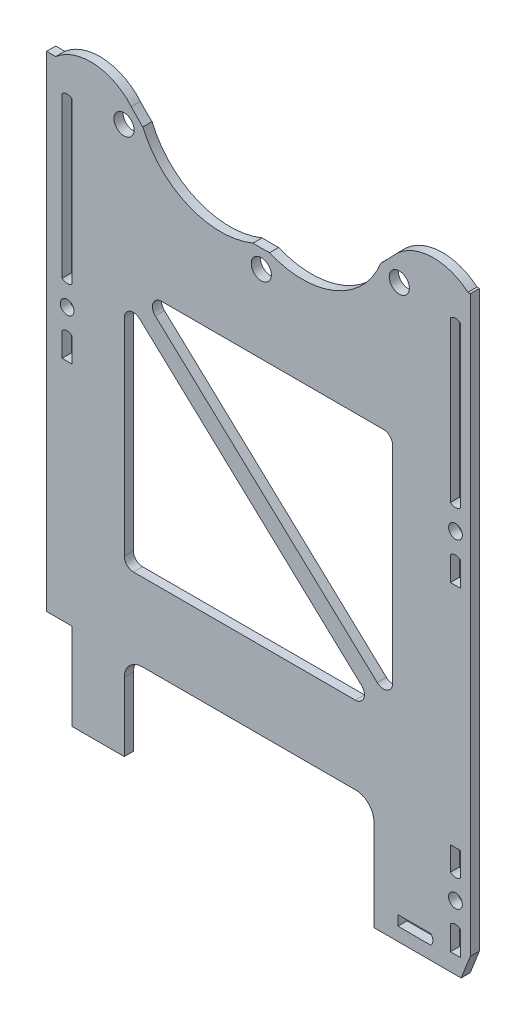
SolidWorks part; units mm, degrees
ref_plane "前视基准面" through (0, 0, 0) normal (0, 0, 1) x (1, 0, 0)
ref_plane "上视基准面" through (0, 0, 0) normal (0, 1, 0) x (1, 0, 0)
ref_plane "右视基准面" through (0, 0, 0) normal (1, 0, 0) x (0, 0, -1)
sketch "草图3" plane through (0, 0, 0) normal (0, 0, 1) x (1, 0, 0)
  line L8 (-41.4, -74.8902) -> (-41.4, -93.8902)
  line L12 (-42.5, -14.9402) -> (-41.8015, -14.9402) construction
  line L111 (-43.6, -9.9902) -> (-43.6, 25.0098)
  line L119 (-41.4, -19.8902) -> (-41.4, -25.1902)
  line L120 (-41.4, -25.1902) -> (-43.6, -25.1902)
  line L121 (-43.6, -25.1902) -> (-43.6, -19.8902)
  line L124 (37.1, -93.8902) -> (29.9, -93.8902)
  line L136 (37.1, -96.0902) -> (29.9, -96.0902)
  line L147 (30, -93.9902) -> (30, -95.9902) construction
  line L148 (29.9, -96.0902) -> (29.9, -93.8902)
  line L152 (-41.4, 25.0098) -> (-41.4, -9.9902)
  line L153 (37, -96.0902) -> (37.1, -96.0902) construction
  line L154 (37, -93.9902) -> (37, -95.9902) construction
  line L155 (37, -95.9902) -> (37, -96.0902) construction
  line L157 (43.6, -25.1902) -> (43.6, -19.8902)
  line L158 (41.4, -25.1902) -> (43.6, -25.1902)
  line L159 (41.4, -19.8902) -> (41.4, -25.1902)
  line L180 (0, 10.5098) -> (0, 13.5) construction
  line L187 (24.6413, -97.9902) -> (24.6413, -93.8902)
  line L198 (24.6413, -97.9902) -> (24.6413, -98.9902)
  line L199 (24.6413, -98.9902) -> (43.7413, -98.9902)
  line L209 (42.5, -9.9902) -> (42.5, -19.8902) construction
  line L212 (0, 56) -> (31.7001, 27.6918) construction
  line L213 (0, 56) -> (28.5728, 24.6019) construction
  line L218 (-45, 31.3171) -> (-47, 31.3171)
  line L221 (45.23, 31.7412) -> (45.7413, 31.7412)
  line L223 (45.7413, -93.8902) -> (43.7413, -98.9902)
  line L224 (45.7413, 31.7412) -> (45.7413, -93.8902)
  line L227 (43.6, -80.0902) -> (41.4, -74.8902) construction
  line L228 (43.6, -74.8902) -> (41.4, -80.0902) construction
  line L229 (42.5, -79.9902) -> (42.5, -74.9902) construction
  line L230 (43.6, -80.0902) -> (43.6, -89.8902) construction
  line L231 (43.6, -95.1902) -> (43.6, -89.8902)
  line L232 (41.4, -95.1902) -> (43.6, -95.1902)
  line L233 (41.4, -89.8902) -> (41.4, -95.1902)
  line L234 (41.4, -74.8902) -> (41.4, -80.0902)
  line L235 (43.6, -74.8902) -> (43.6, -80.0902)
  line L236 (43.6, -74.8902) -> (41.4, -74.8902)
  line L237 (42.5, -79.9902) -> (42.5, -89.8902) construction
  line L239 (-47, 31.3171) -> (-47, -74.8902)
  line L240 (-47, -74.8902) -> (-41.4, -74.8902)
  line L249 (-30, -93.8902) -> (-30, -78.8902)
  line L251 (41.4, 25.0098) -> (41.4, -9.9902)
  line L254 (43.6, -9.9902) -> (43.6, 25.0098)
  line L259 (-32, -1.5) -> (30.7413, -1.5) construction
  line L260 (-32, -1.5) -> (-32, -59.8902) construction
  line L261 (-32, -59.8902) -> (30.7413, -59.8902) construction
  line L262 (30.7413, -1.5) -> (30.7413, -59.8902) construction
  line L263 (24.6413, -78.8902) -> (24.6413, -93.8902)
  line L264 (-32, -1.5) -> (30.7413, -59.8902) construction
  line L265 (-21.8305, -3.5) -> (26.7413, -3.5)
  line L266 (28.7413, -5.5) -> (28.7413, -50.7034)
  line L267 (-23.1931, -6.9641) -> (25.3787, -52.1675)
  line L268 (-26.6375, -9.2228) -> (21.9343, -54.4261)
  line L269 (-28, -57.8902) -> (20.5718, -57.8902)
  line L270 (-30, -10.6868) -> (-30, -55.8902)
  line L271 (28.7413, -3.5) -> (28.7413, -55.2968) construction
  line L272 (-26.9153, -3.5) -> (28.7413, -3.5) construction
  line L273 (-26.9153, -3.5) -> (28.7413, -55.2968) construction
  line L274 (-30, -6.0934) -> (25.6565, -57.8902) construction
  line L275 (-30, -57.8902) -> (25.6565, -57.8902) construction
  line L276 (-30, -6.0934) -> (-30, -57.8902) construction
  line L277 (-41.4, -93.8902) -> (-30, -93.8902)
  line L278 (-26, -74.8902) -> (20.6413, -74.8902)
  arc A14 (-43.6, -19.8902) -> (-41.4, -19.8902) centre (-42.5, -20.9902) cw
  arc A15 (41.4, -19.8902) -> (43.6, -19.8902) centre (42.5, -20.9902) cw
  circle A17 centre (0, 13.5) radius 2.2
  circle A18 centre (-30.052, 25.948) radius 2.2
  circle A24 centre (30.2, 26.0826) radius 2.2
  arc A29 (37.1, -93.8902) -> (37.1, -96.0902) centre (36, -94.9902) cw
  circle A40 centre (42.5, -14.9402) radius 1.5
  circle A41 centre (-42.5, -14.9402) radius 1.5
  arc A43 (-25.9127, 27.5258) -> (-1.8098, 17.5426) centre (-8.8696, 34.5856) ccw
  arc A44 (1.8098, 17.5426) -> (26.1792, 27.7706) centre (9.013, 34.5255) ccw
  arc A46 (-25.9127, 27.5258) -> (-28.4742, 30.0873) centre (0, 56) cw
  arc A47 (-1.8098, 17.5426) -> (1.8098, 17.5426) centre (0, 56) ccw
  circle A52 centre (0, 56) radius 38.5 construction
  circle A53 centre (0, 56) radius 42.5 construction
  arc A54 (26.1792, 27.7706) -> (28.7166, 30.3561) centre (0, 56) ccw
  arc A55 (28.7166, 30.3561) -> (45.23, 31.7412) centre (37.6658, 22.7919) cw
  arc A56 (-28.4742, 30.0873) -> (-45, 31.3171) centre (-37.352, 22.4393) ccw
  arc A58 (41.4, -89.8902) -> (43.6, -89.8902) centre (42.5, -90.9902) cw
  arc A59 (41.4, -80.0902) -> (43.6, -80.0902) centre (42.5, -78.9902) ccw
  circle A60 centre (42.5, -84.9402) radius 1.5
  arc A64 (-43.6, -9.9902) -> (-41.4, -9.9902) centre (-42.5, -8.8902) ccw
  arc A65 (43.6, -9.9902) -> (41.4, -9.9902) centre (42.5, -8.8902) cw
  arc A66 (-43.6, 25.0098) -> (-41.4, 25.0098) centre (-42.5, 23.9098) cw
  arc A67 (41.4, 25.0098) -> (43.6, 25.0098) centre (42.5, 23.9098) cw
  arc A68 (28.7413, -5.5) -> (26.7413, -3.5) centre (26.7413, -5.5) ccw
  arc A69 (-23.1931, -6.9641) -> (-21.8305, -3.5) centre (-21.8305, -5.5) cw
  arc A70 (25.3787, -52.1675) -> (28.7413, -50.7034) centre (26.7413, -50.7034) ccw
  arc A71 (21.9343, -54.4261) -> (20.5718, -57.8902) centre (20.5718, -55.8902) cw
  arc A72 (-28, -57.8902) -> (-30, -55.8902) centre (-28, -55.8902) cw
  arc A73 (-26.6375, -9.2228) -> (-30, -10.6868) centre (-28, -10.6868) ccw
  arc A74 (-26, -74.8902) -> (-30, -78.8902) centre (-26, -78.8902) ccw
  arc A75 (24.6413, -78.8902) -> (20.6413, -74.8902) centre (20.6413, -78.8902) ccw
  point P17 (-44.2, -74.8902)
  point P128 (42.5, -77.4902)
  dimension "D1" = 106.2073
  dimension "D2" = 92.7413
  dimension "D3" = 85
  dimension "D10" = 2
  dimension "D11" = 4
  dimension "D12" = 4
  dimension "D4" = 15
  dimension "D5" = 15
  dimension "D6" = 15
  dimension "D7" = 15
  dimension "D13" = 5.6
  dimension "D14" = 19
  dimension "D15" = 11.4
  dimension "D8" = 2
  dimension "D9" = 2
extrude "凸台-拉伸1" add sketch "草图3" along normal blind 2
